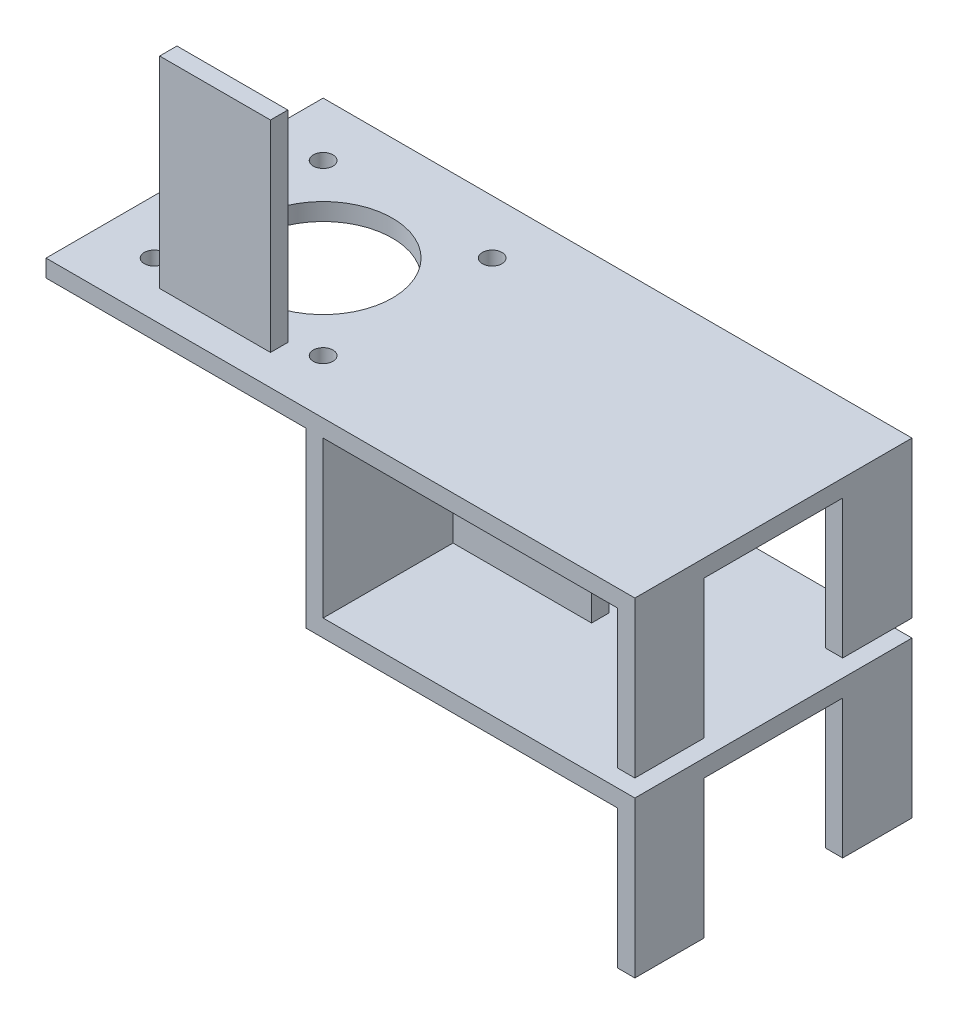
SolidWorks part; units mm, degrees
ref_plane "Front Plane" through (0, 0, 0) normal (0, 0, 1) x (1, 0, 0)
ref_plane "Top Plane" through (0, 0, 0) normal (0, 1, 0) x (1, 0, 0)
ref_plane "Right Plane" through (0, 0, 0) normal (1, 0, 0) x (0, 0, -1)
sketch "Sketch1" plane through (0, 0, 0) normal (0, 1, 0) x (1, 0, 0)
  line L1 (25.4, -25.4) -> (-25.4, -25.4)
  line L2 (25.4, -25.4) -> (25.4, 25.4)
  line L3 (25.4, 25.4) -> (-25.4, 25.4)
  line L4 (-25.4, -25.4) -> (-25.4, 25.4)
  line L5 (25.4, -25.4) -> (-25.4, 25.4) construction
  line L6 (25.4, 25.4) -> (-25.4, -25.4) construction
  point P0 (0, 0)
  dimension "D1" = 50.8
extrude "Boss-Extrude1" add sketch "Sketch1" along normal blind 3.175
sketch "Sketch2" plane through (0, 3.175, 0) normal (0, 1, 0) x (1, 0, 0)
  line L1 (15.494, -15.494) -> (-15.494, -15.494) construction
  line L2 (15.494, -15.494) -> (15.494, 15.494) construction
  line L3 (15.494, 15.494) -> (-15.494, 15.494) construction
  line L4 (-15.494, -15.494) -> (-15.494, 15.494) construction
  line L5 (15.494, -15.494) -> (-15.494, 15.494) construction
  line L6 (15.494, 15.494) -> (-15.494, -15.494) construction
  circle A0 centre (0, 0) radius 12.7
  circle A1 centre (-15.494, 15.494) radius 1.8034
  circle A2 centre (15.494, 15.494) radius 1.8034
  circle A3 centre (15.494, -15.494) radius 1.8034
  circle A4 centre (-15.494, -15.494) radius 1.8034
  dimension "D1" = 25.4
  dimension "D3" = 3.6068
  dimension "D2" = 30.988
extrude "Cut-Extrude1" cut sketch "Sketch2" against normal through all
sketch "Sketch6" plane through (0, 3.175, 0) normal (0, 1, 0) x (1, 0, 0)
  line L1 (-10.16, -16.637) -> (10.16, -16.637)
  line L2 (-10.16, -16.637) -> (-10.16, -19.812)
  line L3 (-10.16, -19.812) -> (10.16, -19.812)
  line L4 (10.16, -16.637) -> (10.16, -19.812)
  circle A1 centre (0, 0) radius 12.7 construction
  point P4 (0, -16.637)
  point P8 (0, -12.7)
  dimension "D1" = 3.175
  dimension "D2" = 16.637
  dimension "D3" = 20.32
extrude "Boss-Extrude4" add sketch "Sketch6" along normal blind 36.9062
sketch "Sketch7" plane through (0, 0, 16.637) normal (0, 0, -1) x (-1, 0, 0)
  line L0 (-10.16, 40.0812) -> (12.7, 3.175) construction
  circle A0 centre (1.27, 21.6281) radius 3.1115
  dimension "D1" = 6.223
extrude "Boss-Extrude5" add sketch "Sketch7" along normal blind 5.08
sketch "Sketch11" plane through (0, 0, 0) normal (0, -1, 0) x (1, 0, 0)
  line L0 (25.4, -25.4) -> (-25.4, -25.4) construction
  line L1 (25.4, 25.4) -> (22.225, 25.4)
  line L2 (25.4, 25.4) -> (25.4, -25.4)
  line L3 (25.4, -25.4) -> (22.225, -25.4)
  line L4 (22.225, 25.4) -> (22.225, -25.4)
  dimension "D1" = 3.175
extrude "Boss-Extrude8" add sketch "Sketch11" along normal blind 31.75
sketch "Sketch13" plane through (25.4, 0, 0) normal (1, 0, 0) x (0, 0, -1)
  line L0 (25.4, 3.175) -> (25.4, -31.75) construction
  line L1 (-25.4, -31.75) -> (25.4, -31.75)
  line L2 (-25.4, -31.75) -> (-25.4, -28.575)
  line L3 (-25.4, -28.575) -> (25.4, -28.575)
  line L4 (25.4, -31.75) -> (25.4, -28.575)
  line L5 (-25.4, 3.175) -> (-25.4, -31.75) construction
  line L6 (25.4, 3.175) -> (-25.4, 3.175)
  line L7 (25.4, 3.175) -> (25.4, 0)
  line L8 (25.4, 0) -> (-25.4, 0)
  line L9 (-25.4, 3.175) -> (-25.4, 0)
  dimension "D1" = 3.175
extrude "Boss-Extrude10" add sketch "Sketch13" along normal blind 57.15
sketch "Sketch15" plane through (0, -31.75, 0) normal (0, -1, 0) x (1, 0, 0)
  line L1 (82.55, 25.4) -> (79.375, 25.4)
  line L2 (82.55, 25.4) -> (82.55, 12.7)
  line L3 (82.55, 12.7) -> (79.375, 12.7)
  line L4 (79.375, 25.4) -> (79.375, 12.7)
  line L5 (82.55, -25.4) -> (79.375, -25.4)
  line L6 (82.55, -25.4) -> (82.55, -12.7)
  line L7 (82.55, -12.7) -> (79.375, -12.7)
  line L8 (79.375, -25.4) -> (79.375, -12.7)
  dimension "D1" = 12.7
  dimension "D2" = 3.175
extrude "Boss-Extrude12" add sketch "Sketch15" along normal blind 25.4
sketch "Sketch16" plane through (0, 0, 0) normal (0, -1, 0) x (1, 0, 0)
  line L0 (82.55, -25.4) -> (82.55, -12.7) construction
  line L1 (82.55, -12.7) -> (79.375, -12.7) construction
  line L2 (79.375, -12.7) -> (79.375, -25.4) construction
  line L3 (79.375, -25.4) -> (82.55, -25.4) construction
  line L4 (82.55, 12.7) -> (82.55, 25.4) construction
  line L5 (82.55, 25.4) -> (79.375, 25.4) construction
  line L6 (79.375, 25.4) -> (79.375, 12.7) construction
  line L7 (79.375, 12.7) -> (82.55, 12.7) construction
  line L8 (82.55, -25.4) -> (82.55, -12.7)
  line L9 (82.55, -12.7) -> (79.375, -12.7)
  line L10 (79.375, -12.7) -> (79.375, -25.4)
  line L11 (79.375, -25.4) -> (82.55, -25.4)
  line L12 (82.55, 12.7) -> (82.55, 25.4)
  line L13 (82.55, 25.4) -> (79.375, 25.4)
  line L14 (79.375, 25.4) -> (79.375, 12.7)
  line L15 (79.375, 12.7) -> (82.55, 12.7)
extrude "Boss-Extrude13" add sketch "Sketch16" along normal blind 25.4
sketch "Sketch17" plane through (25.4, 0, 0) normal (1, 0, 0) x (0, 0, -1)
  line L0 (-25.4, 0) -> (25.4, 0) construction
  line L1 (-1.5875, 0) -> (1.5875, 0)
  line L2 (-1.5875, 0) -> (-1.5875, -28.575)
  line L3 (-1.5875, -28.575) -> (1.5875, -28.575)
  line L4 (1.5875, 0) -> (1.5875, -28.575)
  line L5 (25.4, -28.575) -> (-25.4, -28.575) construction
  point P8 (0, 0)
  dimension "D1" = 3.175
extrude "Boss-Extrude14" add sketch "Sketch17" along normal blind 25.4
